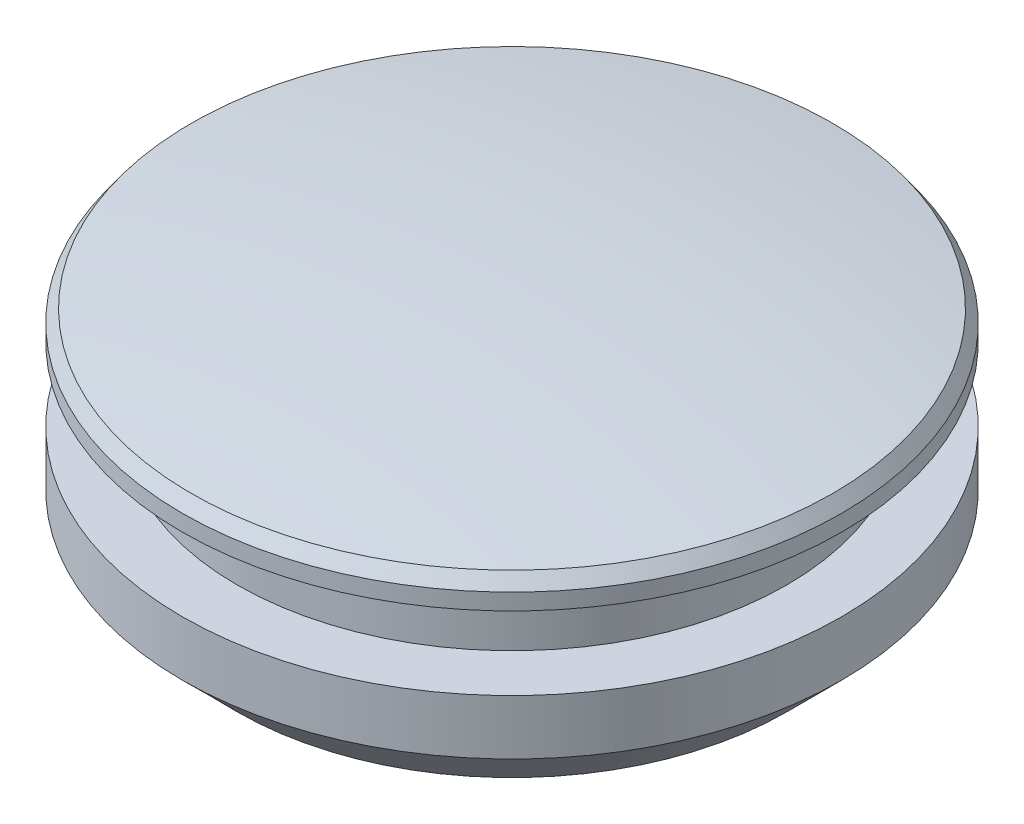
SolidWorks part; units mm, degrees
ref_plane "Front Plane" through (0, 0, 0) normal (0, 0, 1) x (1, 0, 0)
ref_plane "Top Plane" through (0, 0, 0) normal (0, 1, 0) x (1, 0, 0)
ref_plane "Right Plane" through (0, 0, 0) normal (1, 0, 0) x (0, 0, -1)
sketch "Sketch1" plane through (0, 0, 0) normal (0, 0, 1) x (1, 0, 0)
  line L0 (-6, 0) -> (-7.5, 0)
  line L1 (-7.5, 0) -> (-9, 1.5)
  line L2 (-9, 1.5) -> (-9, 3)
  line L3 (-9, 3) -> (-7.5, 3)
  line L4 (-7.5, 3) -> (-7.5, 5)
  line L5 (-7.5, 5) -> (-9, 5)
  line L7 (-9, 6.5) -> (0, 6.5) construction
  line L8 (0, 6.5) -> (0, 5)
  line L9 (0, -1000) -> (0, 0) construction
  line L10 (-9, 5.75) -> (-9, 6.5) construction
  line L11 (-9, 5.75) -> (-9, 5)
  line L12 (-6, 0) -> (-6, 3)
  line L13 (0, 0) -> (-6, 0) construction
  line L14 (0, 5) -> (0, 0) construction
  line L15 (0, 0) -> (0, 5) construction
  line L16 (0, 5) -> (0, 49000) construction
  arc A1 (0, 6.5) -> (-9, 5.75) centre (0, -47.875) ccw
  ellipse E0 centre (0, 3) end of major axis (6, 3) minor radius 2 (0, 5) -> (-6, 3) ccw
  point P11 (0, 0)
  point P22 (-5.7244, 0)
  point P24 (0, 0)
  point P25 (6, 3)
  dimension "D1" = 2
  dimension "D2" = 15
  dimension "D3" = 1.5
  dimension "D4" = 1.5
  dimension "D5" = 1.5
  dimension "D6" = 45
  dimension "D7" = 1.5
revolve "Revolve1" add sketch "Sketch1" angle 360 about L9
chamfer "Chamfer1" distance 0.25 angle 45 2 edges at (9, 5.75, 0) (6, 0, 0)
